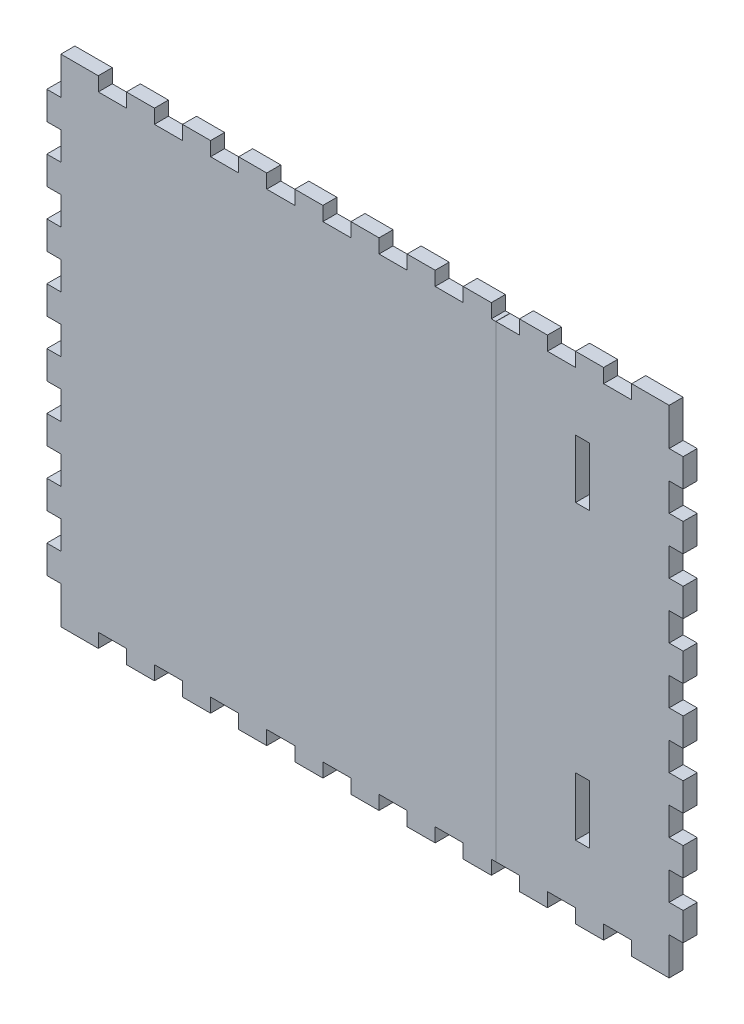
SolidWorks part; units mm, degrees
ref_plane "Front Plane" through (0, 0, 0) normal (0, 0, 1) x (1, 0, 0)
ref_plane "Top Plane" through (0, 0, 0) normal (0, 1, 0) x (1, 0, 0)
ref_plane "Right Plane" through (0, 0, 0) normal (1, 0, 0) x (0, 0, -1)
sketch "Model" plane through (0, 0, 0) normal (0, 0, 1) x (1, 0, 0)
  line L0 (221, 215) -> (221, 199)
  line L1 (221, 199) -> (215, 199)
  line L2 (215, 199) -> (215, 187)
  line L3 (215, 187) -> (221, 187)
  line L4 (221, 187) -> (221, 175)
  line L5 (221, 175) -> (215, 175)
  line L6 (215, 175) -> (215, 163)
  line L7 (215, 163) -> (221, 163)
  line L8 (221, 163) -> (221, 151)
  line L9 (221, 151) -> (215, 151)
  line L10 (215, 151) -> (215, 139)
  line L11 (215, 139) -> (221, 139)
  line L12 (221, 139) -> (221, 127)
  line L13 (221, 127) -> (215, 127)
  line L14 (215, 127) -> (215, 115)
  line L15 (215, 115) -> (221, 115)
  line L16 (221, 115) -> (221, 103)
  line L17 (221, 103) -> (215, 103)
  line L18 (215, 103) -> (215, 91)
  line L19 (215, 91) -> (221, 91)
  line L20 (221, 91) -> (221, 79)
  line L21 (221, 79) -> (215, 79)
  line L22 (215, 79) -> (215, 67)
  line L23 (215, 67) -> (221, 67)
  line L24 (221, 67) -> (221, 55)
  line L25 (221, 55) -> (215, 55)
  line L26 (215, 55) -> (215, 43)
  line L27 (215, 43) -> (221, 43)
  line L28 (221, 43) -> (221, 31)
  line L29 (221, 31) -> (215, 31)
  line L30 (215, 31) -> (215, 19)
  line L31 (215, 19) -> (221, 19)
  line L32 (221, 19) -> (221, 3)
  line L33 (221, 3) -> (237, 3)
  line L34 (237, 3) -> (237, 9)
  line L35 (237, 9) -> (249, 9)
  line L36 (249, 9) -> (249, 3)
  line L37 (249, 3) -> (261, 3)
  line L38 (261, 3) -> (261, 9)
  line L39 (261, 9) -> (273, 9)
  line L40 (273, 9) -> (273, 3)
  line L41 (273, 3) -> (285, 3)
  line L42 (285, 3) -> (285, 9)
  line L43 (285, 9) -> (297, 9)
  line L44 (297, 9) -> (297, 3)
  line L45 (297, 3) -> (309, 3)
  line L46 (309, 3) -> (309, 9)
  line L47 (309, 9) -> (321, 9)
  line L48 (321, 9) -> (321, 3)
  line L49 (321, 3) -> (333, 3)
  line L50 (333, 3) -> (333, 9)
  line L51 (333, 9) -> (345, 9)
  line L52 (345, 9) -> (345, 3)
  line L53 (345, 3) -> (357, 3)
  line L54 (357, 3) -> (357, 9)
  line L55 (357, 9) -> (369, 9)
  line L56 (369, 9) -> (369, 3)
  line L57 (369, 3) -> (381, 3)
  line L58 (381, 3) -> (381, 9)
  line L59 (381, 9) -> (393, 9)
  line L60 (393, 9) -> (393, 3)
  line L61 (393, 3) -> (405, 3)
  line L62 (405, 3) -> (405, 9)
  line L63 (405, 9) -> (417, 9)
  line L64 (417, 9) -> (417, 3)
  line L65 (417, 3) -> (429, 3)
  line L66 (429, 3) -> (429, 9)
  line L67 (429, 9) -> (441, 9)
  line L68 (441, 9) -> (441, 3)
  line L69 (441, 3) -> (453, 3)
  line L70 (453, 3) -> (453, 9)
  line L71 (453, 9) -> (465, 9)
  line L72 (465, 9) -> (465, 3)
  line L73 (465, 3) -> (477, 3)
  line L74 (477, 3) -> (481, 3)
  line L75 (481, 3) -> (481, 19)
  line L76 (481, 19) -> (487, 19)
  line L77 (487, 19) -> (487, 31)
  line L78 (487, 31) -> (481, 31)
  line L79 (481, 31) -> (481, 43)
  line L80 (481, 43) -> (487, 43)
  line L81 (487, 43) -> (487, 55)
  line L82 (487, 55) -> (481, 55)
  line L83 (481, 55) -> (481, 67)
  line L84 (481, 67) -> (487, 67)
  line L85 (487, 67) -> (487, 79)
  line L86 (487, 79) -> (481, 79)
  line L87 (481, 79) -> (481, 91)
  line L88 (481, 91) -> (487, 91)
  line L89 (487, 91) -> (487, 103)
  line L90 (487, 103) -> (481, 103)
  line L91 (481, 103) -> (481, 115)
  line L92 (481, 115) -> (487, 115)
  line L93 (487, 115) -> (487, 127)
  line L94 (487, 127) -> (481, 127)
  line L95 (481, 127) -> (481, 139)
  line L96 (481, 139) -> (487, 139)
  line L97 (487, 139) -> (487, 151)
  line L98 (487, 151) -> (481, 151)
  line L99 (481, 151) -> (481, 163)
  line L100 (481, 163) -> (487, 163)
  line L101 (487, 163) -> (487, 175)
  line L102 (487, 175) -> (481, 175)
  line L103 (481, 175) -> (481, 187)
  line L104 (481, 187) -> (487, 187)
  line L105 (487, 187) -> (487, 199)
  line L106 (487, 199) -> (481, 199)
  line L107 (481, 199) -> (481, 215)
  line L108 (481, 215) -> (465, 215)
  line L109 (465, 215) -> (465, 209)
  line L110 (465, 209) -> (453, 209)
  line L111 (453, 209) -> (453, 215)
  line L112 (453, 215) -> (441, 215)
  line L113 (441, 215) -> (441, 209)
  line L114 (441, 209) -> (429, 209)
  line L115 (429, 209) -> (429, 215)
  line L116 (429, 215) -> (417, 215)
  line L117 (417, 215) -> (417, 209)
  line L118 (417, 209) -> (405, 209)
  line L119 (405, 209) -> (405, 215)
  line L120 (405, 215) -> (393, 215)
  line L121 (393, 215) -> (393, 209)
  line L122 (393, 209) -> (381, 209)
  line L123 (381, 209) -> (381, 215)
  line L124 (381, 215) -> (369, 215)
  line L125 (369, 215) -> (369, 209)
  line L126 (369, 209) -> (357, 209)
  line L127 (357, 209) -> (357, 215)
  line L128 (357, 215) -> (345, 215)
  line L129 (345, 215) -> (345, 209)
  line L130 (345, 209) -> (333, 209)
  line L131 (333, 209) -> (333, 215)
  line L132 (333, 215) -> (321, 215)
  line L133 (321, 215) -> (321, 209)
  line L134 (321, 209) -> (309, 209)
  line L135 (309, 209) -> (309, 215)
  line L136 (309, 215) -> (297, 215)
  line L137 (297, 215) -> (297, 209)
  line L138 (297, 209) -> (285, 209)
  line L139 (285, 209) -> (285, 215)
  line L140 (285, 215) -> (273, 215)
  line L141 (273, 215) -> (273, 209)
  line L142 (273, 209) -> (261, 209)
  line L143 (261, 209) -> (261, 215)
  line L144 (261, 215) -> (249, 215)
  line L145 (249, 215) -> (249, 209)
  line L146 (249, 209) -> (237, 209)
  line L147 (237, 209) -> (237, 215)
  line L148 (237, 215) -> (225, 215)
  line L149 (225, 215) -> (221, 215)
extrude "Boss-Extrude1" add sketch "Model" along normal blind 6
sketch "Sketch2" plane through (0, 0, 6) normal (0, 0, 1) x (1, 0, 0)
  line L0 (481, 175) -> (481, 187) construction
  line L1 (406.9, 237.0674) -> (407, 237.0674)
  line L2 (406.9, 237.0674) -> (406.9, -28.447)
  line L3 (406.9, -28.447) -> (407, -28.447)
  line L4 (407, 237.0674) -> (407, -28.447)
  line L5 (473, 215) -> (473, 3)
  line L6 (441, 184) -> (447, 184)
  line L7 (441, 184) -> (441, 159)
  line L8 (441, 159) -> (447, 159)
  line L9 (447, 184) -> (447, 159)
  line L10 (481, 215) -> (465, 215) construction
  line L11 (465, 3) -> (481, 3) construction
  line L12 (473, 3) -> (473, 109)
  line L13 (473, 109) -> (406.9, 109)
  line L14 (447, 171.5) -> (481, 171.5)
  line L15 (481, 151) -> (481, 163) construction
  line L16 (441, 171.5) -> (407, 171.5)
  line L17 (441, 59) -> (447, 59)
  line L18 (447, 34) -> (447, 59)
  line L19 (441, 34) -> (447, 34)
  line L20 (441, 34) -> (441, 59)
  dimension "D1" = 0.1
  dimension "D2" = 74
  dimension "D3" = 6
  dimension "D4" = 25
  dimension "D5" = 50
extrude "Cut-Extrude1" cut sketch "Sketch2" against normal blind 6 contours L9 L8 L7 L6 | L18 L17 L20 L19 | L2 L1 L4 L3
